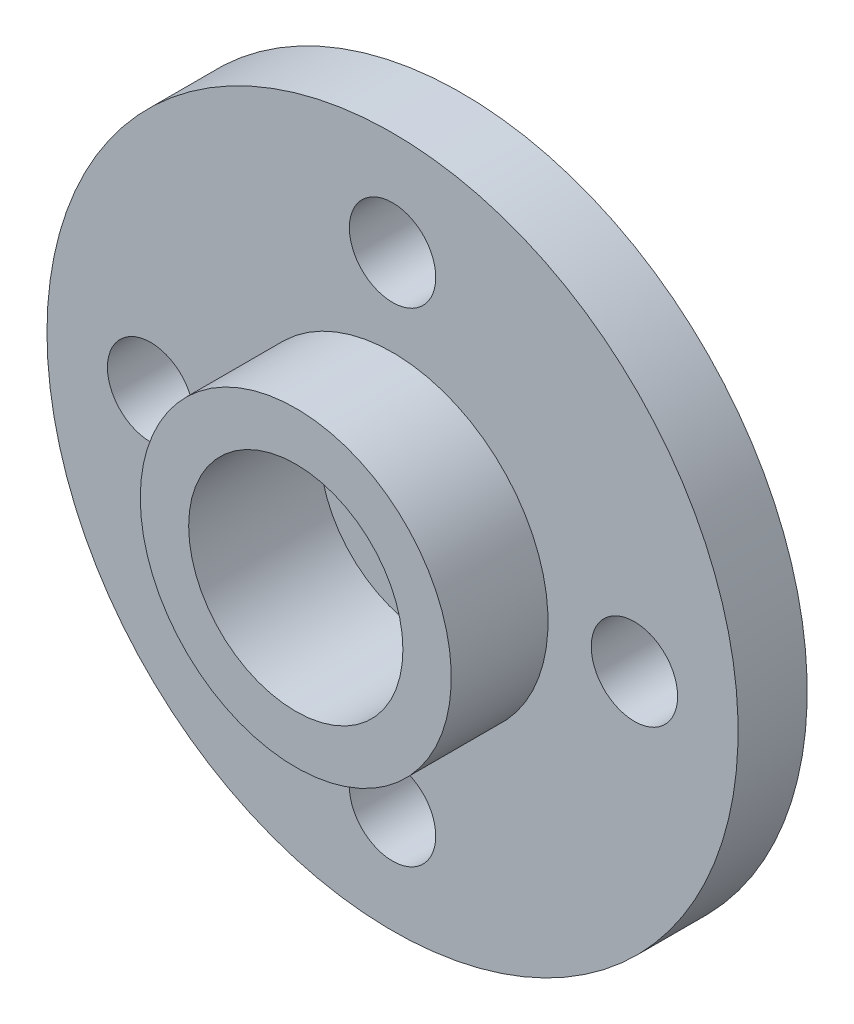
SolidWorks part; units mm, degrees
ref_plane "Front Plane" through (0, 0, 0) normal (0, 0, 1) x (1, 0, 0)
ref_plane "Top Plane" through (0, 0, 0) normal (0, 1, 0) x (1, 0, 0)
ref_plane "Right Plane" through (0, 0, 0) normal (1, 0, 0) x (0, 0, -1)
ref_plane "基准面1" through (0, -19.9, 0) normal (0, -1, 0) x (1, 0, 0)
sketch "草图1" plane through (0, -19.9, 0) normal (0, -1, 0) x (1, 0, 0)
  line L0 (-29.1026, -34.124) -> (-39.1026, -34.124)
  line L1 (-39.1026, -34.124) -> (-39.1026, -36.124)
  line L2 (-39.1026, -36.124) -> (-29.1026, -36.124)
  line L3 (-29.1026, -36.124) -> (-29.1026, -34.124)
  line L4 (-39.1026, -34.124) -> (-39.1026, -36.124) construction
revolve "旋转1" add sketch "草图1" angle 360 about L4
sketch "草图2" plane through (0, 0, -34.124) normal (0, 0, 1) x (1, 0, 0)
  circle A0 centre (-39.1026, -19.9) radius 4.5
extrude "凸台-拉伸1" add sketch "草图2" along normal blind 2.8
hole_wizard "Ø2.5 (2.5) 直径孔1" positions "草图4" profile "草图3" hole size "Ø2.5" standard "ANSI Metric"
sketch "草图4" plane through (0, 0, -36.124) normal (0, 0, -1) x (-1, 0, 0)
  point P0 (46.1026, -19.9)
  point P1 (39.1026, -12.9)
  point P2 (32.1026, -19.9)
  point P3 (39.1026, -26.9)
sketch "草图3" plane through (-46.1026, -19.9, -36.124) normal (1, 0, 0) x (0, 1, 0)
  line L0 (0, 0) -> (0, 4.8)
  line L1 (0, 4.8) -> (1.25, 4.8)
  line L2 (1.25, 4.8) -> (1.25, 0)
  line L5 (1.25, 0) -> (0, 0)
  line L11 (0, -6.35) -> (0, 107.95) construction
  dimension "通孔孔直径" = 2.5
  dimension "通孔孔深度" = 4.8
hole_wizard "M3 六角头机械螺钉的柱形沉头孔1" positions "草图6" profile "草图5" counterbore size "M3" standard "ANSI Metric"
sketch "草图6" plane through (0, 0, -31.324) normal (0, 0, 1) x (1, 0, 0)
  point P0 (-39.1026, -19.9)
sketch "草图5" plane through (-39.1026, -19.9, -31.324) normal (1, 0, 0) x (0, -1, 0)
  line L0 (0, 0) -> (0, 4.8)
  line L1 (0, 4.8) -> (1.6, 4.8)
  line L3 (1.6, 4.8) -> (1.6, 3.8)
  line L4 (1.6, 3.8) -> (3.1, 3.8)
  line L5 (3.1, 3.8) -> (3.1, 0)
  line L7 (3.1, 0) -> (0, 0)
  line L11 (0, -6.35) -> (0, 107.95) construction
  dimension "通孔孔直径" = 3.2
  dimension "通孔孔深度" = 4.8
  dimension "柱形沉头孔直径" = 6.2
  dimension "柱形沉头孔深度" = 3.8
